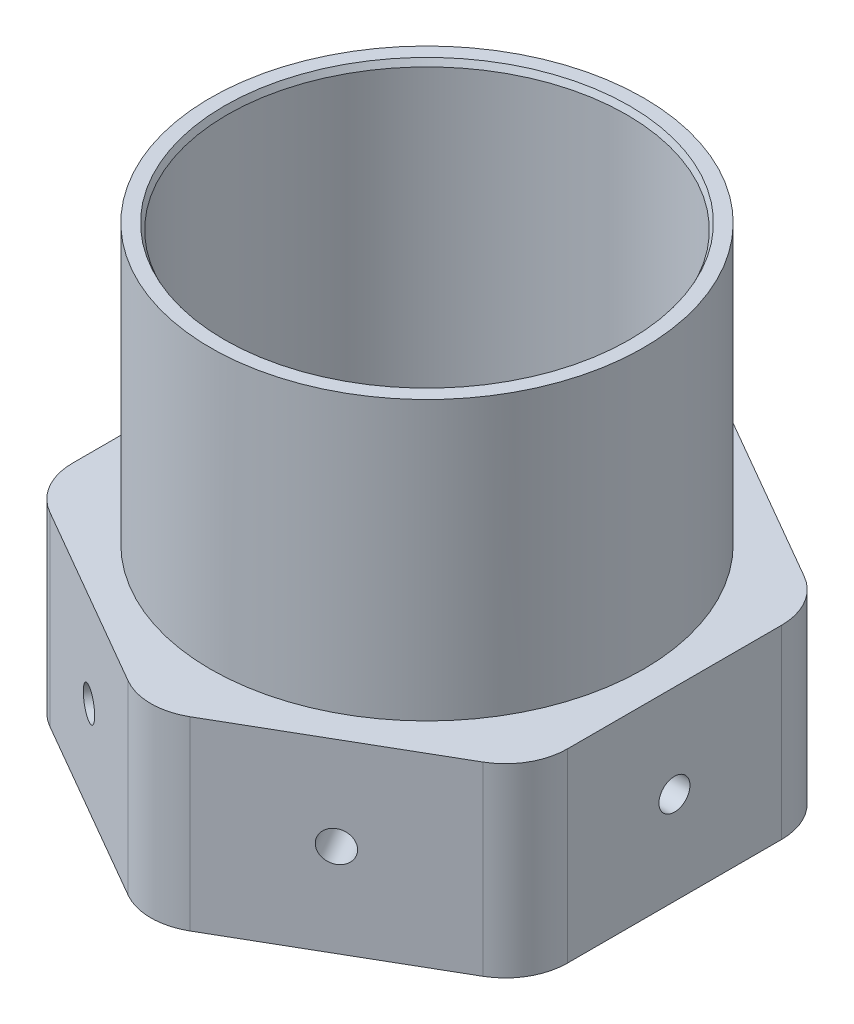
SolidWorks part; units mm, degrees
ref_plane "Front Plane" through (0, 0, 0) normal (0, 0, 1) x (1, 0, 0)
ref_plane "Top Plane" through (0, 0, 0) normal (0, 1, 0) x (1, 0, 0)
ref_plane "Right Plane" through (0, 0, 0) normal (1, 0, 0) x (0, 0, -1)
sketch "Sketch1" plane through (0, 0, 0) normal (0, 1, 0) x (1, 0, 0)
  line L9 (0, -58.6588) -> (50.8, -29.3294)
  line L10 (50.8, -29.3294) -> (50.8, 29.3294)
  line L11 (50.8, 29.3294) -> (0, 58.6588)
  line L12 (0, 58.6588) -> (-50.8, 29.3294)
  line L13 (-50.8, 29.3294) -> (-50.8, -29.3294)
  line L14 (-50.8, -29.3294) -> (0, -58.6588)
  circle A0 centre (0, 0) radius 40.9956
  circle A1 centre (0, 0) radius 50.8 construction
  dimension "D2" = 81.9912
  dimension "D1" = 101.6
extrude "Boss-Extrude1" add sketch "Sketch1" along normal blind 38.1
sketch "Sketch2" plane through (-50.8, 0, 0) normal (-1, 0, 0) x (0, 0, 1)
  circle A0 centre (0, 19.05) radius 3.1813
  dimension "D1" = 6.3627
extrude "Cut-Extrude1" cut sketch "Sketch2" against normal blind 29.464 contours A0
pattern_circular "CirPattern1" count 6 over 360 about axis through (0, 38.1, 0) along (0, 1, 0) of "Cut-Extrude1"
ref_plane "Plane1" through (-50.8, 38.1, -29.3294) normal (0, -1, 0) x (-1, 0, 0)
sketch "Sketch3" plane through (-50.8, 38.1, -29.3294) normal (0, -1, 0) x (1, 0, 0)
  circle A0 centre (50.8, 29.3294) radius 40.9956
  circle A1 centre (50.8, 29.3294) radius 44.45
  circle A2 centre (50.8, 29.3294) radius 40.9956 construction
  dimension "D1" = 88.9
extrude "Boss-Extrude2" add sketch "Sketch3" against normal blind 57.15
fillet "Fillet1" radius 12.7 6 edges at (-50.8, 19.05, -29.3294) (0, 19.05, -58.6588) (50.8, 19.05, -29.3294) (50.8, 19.05, 29.3294) (-50.8, 19.05, 29.3294) (0, 19.05, 58.6588)
chamfer "Chamfer1" distance 1.27 angle 25 2 edges at (0, 0, 40.9956) (0, 95.25, -40.9956)
equation "\"D2@Sketch1\"=3.2400in-0.012"
